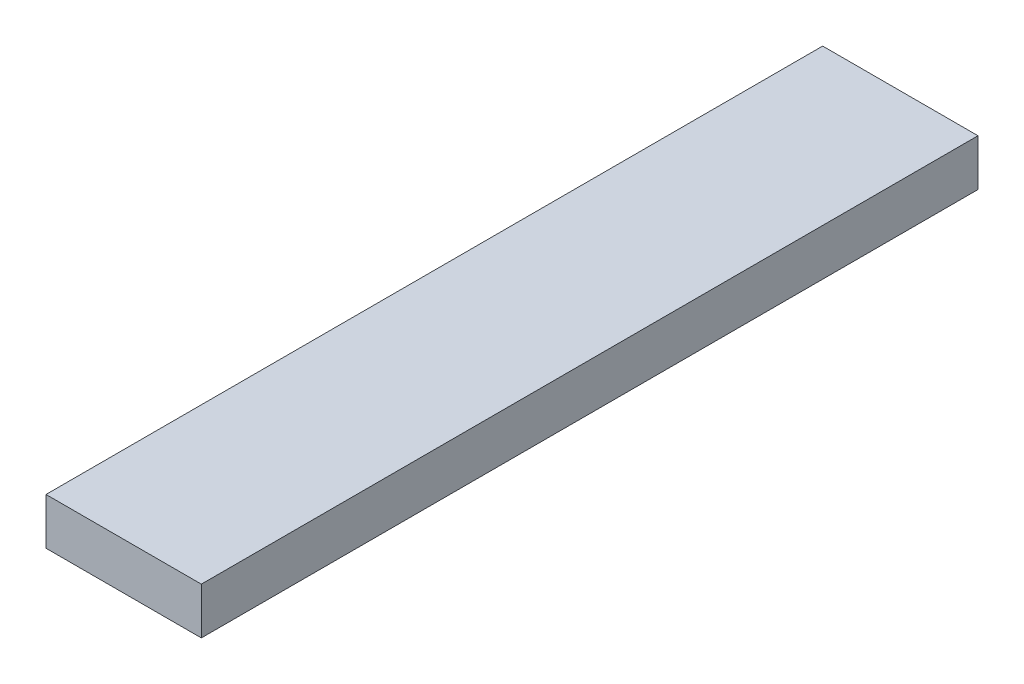
SolidWorks part; units mm, degrees
ref_plane "Front Plane" through (0, 0, 0) normal (0, 0, 1) x (1, 0, 0)
ref_plane "Top Plane" through (0, 0, 0) normal (0, 1, 0) x (1, 0, 0)
ref_plane "Right Plane" through (0, 0, 0) normal (1, 0, 0) x (0, 0, -1)
sketch "Sketch1" plane through (0, 0, 0) normal (0, 1, 0) x (1, 0, 0)
  line L1 (0, 0) -> (10, 0)
  line L2 (0, 0) -> (0, 50)
  line L3 (0, 50) -> (10, 50)
  line L4 (10, 0) -> (10, 50)
  dimension "D1" = 50
  dimension "D2" = 10
extrude "Boss-Extrude1" add sketch "Sketch1" along normal blind 3
